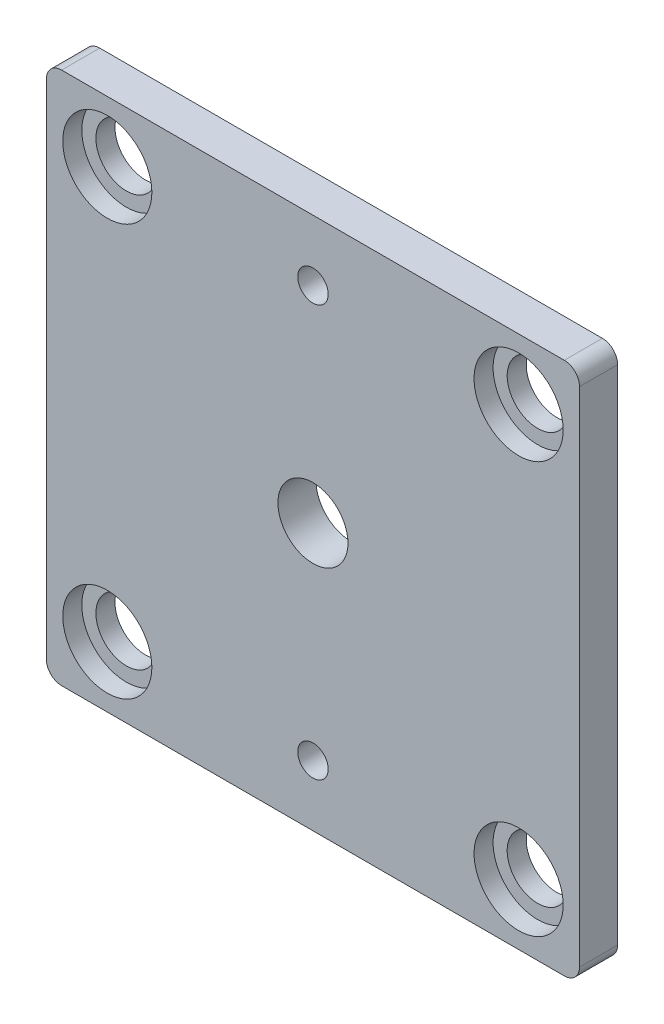
SolidWorks part; units mm, degrees
ref_plane "Front" through (0, 0, 0) normal (0, 0, 1) x (1, 0, 0)
ref_plane "Top" through (0, 0, 0) normal (0, 1, 0) x (1, 0, 0)
ref_plane "Right" through (0, 0, 0) normal (1, 0, 0) x (0, 0, -1)
sketch "Sketch1" plane through (0, 0, 0) normal (0, 0, 1) x (1, 0, 0)
  line L1 (35, -35) -> (-35, -35)
  line L2 (35, -35) -> (35, 35)
  line L3 (35, 35) -> (-35, 35)
  line L4 (-35, -35) -> (-35, 35)
  line L5 (35, -35) -> (-35, 35) construction
  line L6 (35, 35) -> (-35, -35) construction
  circle A4 centre (0, 0) radius 4.6
  circle A5 centre (0, 27) radius 2
  circle A6 centre (0, -27) radius 2
  circle A7 centre (-27, 27) radius 4
  circle A9 centre (27, 27) radius 4
  circle A10 centre (27, -27) radius 4
  circle A11 centre (-27, -27) radius 4
  point P0 (0, 0)
  dimension "D8" = 9.2
  dimension "D9" = 4
  dimension "D10" = 8
  dimension "D1" = 70
  dimension "D2" = 70
  dimension "D7" = 8
extrude "Boss-Extrude1" add sketch "Sketch1" along normal blind 5
fillet "Fillet1" radius 2 3 edges at (35, -35, 2.5) (35, 35, 2.5) (-35, 35, 2.5)
fillet "Fillet2" radius 2 1 edges at (-35, -35, 2.5)
sketch "Sketch2" plane through (0, 0, 5) normal (0, 0, 1) x (1, 0, 0)
  circle A0 centre (-27, 27) radius 5.85
  circle A1 centre (27, 27) radius 5.85
  circle A2 centre (27, -27) radius 5.85
  circle A3 centre (-27, -27) radius 5.85
  dimension "D1" = 11.7
extrude "Cut-Extrude1" cut sketch "Sketch2" against normal blind 2.5
